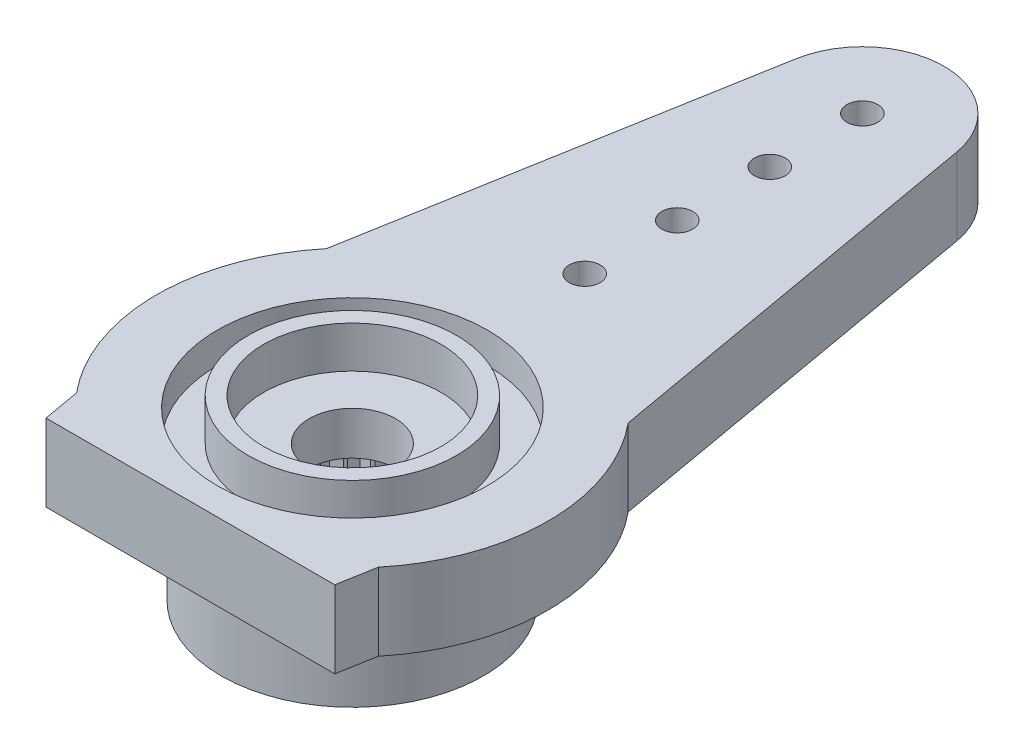
SolidWorks part; units mm, degrees
material "PC High Viscosity"
ref_plane "Front Plane" through (0, 0, 0) normal (0, 0, 1) x (1, 0, 0)
ref_plane "Top Plane" through (0, 0, 0) normal (0, 1, 0) x (1, 0, 0)
ref_plane "Right Plane" through (0, 0, 0) normal (1, 0, 0) x (0, 0, -1)
sketch "BaseS" plane through (0, 0, 0) normal (0, 1, 0) x (1, 0, 0)
  circle A0 centre (0, 0) radius 6.35
  dimension "D1" = 12.7
extrude "BASE" add sketch "BaseS" along normal blind 5.4
sketch "TopBoreS" plane through (0, 5.4, 0) normal (0, 1, 0) x (1, 0, 0)
  circle A0 centre (0, 0) radius 1.4
  dimension "D1" = 2.8
extrude "TOP BORE" cut sketch "TopBoreS" against normal through all
sketch "HornHalfS" plane through (0, 5.4, 0) normal (0, 1, 0) x (1, 0, 0)
  line L0 (0, 0) -> (0, 16.53) construction
  line L1 (-2.6097, 16.9902) -> (-4.8916, 4.049)
  line L2 (0, 19.18) -> (0, 16.53) construction
  line L3 (2.6097, 16.9902) -> (4.8916, 4.049)
  arc A0 (2.6097, 16.9902) -> (-2.6097, 16.9902) centre (0, 16.53) ccw
  arc A1 (4.8916, 4.049) -> (-4.8916, 4.049) centre (0, 0) ccw
  circle A2 centre (0, 0) radius 6.35 construction
  dimension "D1" = 5.3
  dimension "D2" = 19.18
  dimension "D3" = 10
  dimension "D4" = 9.7832
extrude "HORN HALF" add sketch "HornHalfS" against normal blind 2.5
sketch "HornAttachS" plane through (0, 5.4, 0) normal (0, 1, 0) x (1, 0, 0)
  circle A0 centre (0, 16.53) radius 0.5
  dimension "D1" = 1
extrude "HORN ATTACH" cut sketch "HornAttachS" against normal through all
sketch "HA LP RS" plane through (0, 0, 0) normal (0, 1, 0) x (1, 0, 0)
  line L0 (0, 0) -> (0, 16.53) construction
pattern_linear "HA LP" count 4 spacing 3 along (0, 0, 1) of "HORN ATTACH"
mirror "HORN BODIES" about plane through (0, 0, 0) normal (0, 0, 1) of "HA LP", "HORN ATTACH", "HORN HALF"
sketch "ToothS" plane through (0, 0, 0) normal (0, -1, 0) x (1, 0, 0)
  line L0 (0, -2.9) -> (0.2629, -2.5867)
  line L1 (0, -2.9) -> (-0.2629, -2.5867)
  line L2 (0, -2.6) -> (0, -2.9) construction
  line L3 (0, 0) -> (0, -2.6) construction
  arc A0 (-0.2629, -2.5867) -> (0.2629, -2.5867) centre (0, 0) ccw
  dimension "D1" = 5.2
  dimension "D2" = 80
  dimension "D3" = 0.3
extrude "TOOTH" cut sketch "ToothS" against normal blind 3
pattern_circular "TOOTH CP" count 26 over 360 about axis through (0, 0, 0) along (0, 1, 0) of "TOOTH"
sketch "BottomBoreS" plane through (0, 0, 0) normal (0, -1, 0) x (-1, 0, 0)
  circle A0 centre (0, 0) radius 2.6
  arc A1 (0.2629, 2.5867) -> (-0.2629, 2.5867) centre (0, 0) ccw construction
extrude "BOTTOM BORE" cut sketch "BottomBoreS" against normal up to surface (3 mm away) up to face at (-0.6451, 3, 2.6172)
sketch "HoldingShaftS" plane through (0, 0, 0) normal (0, -1, 0) x (1, 0, 0)
  circle A0 centre (0, 0) radius 6.35 construction
  circle A1 centre (0, 0) radius 6.35
  circle A2 centre (0, 0) radius 4.25
  dimension "D1" = 2.1
  dimension "D2" = 8.5
extrude "HOLDING SHAFT" cut sketch "HoldingShaftS" against normal up to surface (2.9 mm away) up to face at (0, 2.9, -13.03)
sketch "TopCutS" plane through (0, 5.4, 0) normal (0, 1, 0) x (1, 0, 0)
  circle A0 centre (0, 0) radius 4.375
  arc A1 (4.8916, -4.049) -> (4.8916, 4.049) centre (0, 0) ccw construction
  dimension "D1" = 1.975
  dimension "D2" = 8.75
extrude "TOP CUT" cut sketch "TopCutS" against normal blind 1
sketch "TopPocketCylinderS" plane through (0, 4.4, 0) normal (0, 1, 0) x (1, 0, 0)
  circle A0 centre (0, 0) radius 2.875
  circle A1 centre (0, 0) radius 3.375
  circle A2 centre (0, 0) radius 4.375 construction
  dimension "D2" = 0.5
  dimension "D1" = 1
  dimension "D3" = 6.75
extrude "TOP POCKET CYLINDER" add sketch "TopPocketCylinderS" along normal offset from surface (1.35 mm away) 0.35 up to face at (0, 5.4, 4.375) offset beyond the face yes
sketch "Sketch1" plane through (0, 5.4, 0) normal (0, 1, 0) x (1, 0, 0)
  line L0 (4.6798, -5.25) -> (2.6097, -16.9902)
  line L1 (-4.6798, -5.25) -> (-2.6097, -16.9902)
  line L3 (-4.6798, -5.25) -> (4.6798, -5.25)
  line L4 (-2.6097, -16.9902) -> (-4.8916, -4.049) construction
  arc A1 (2.6097, -16.9902) -> (-2.6097, -16.9902) centre (0, -16.53) cw
  point P0 (0, -5.25)
  point P11 (-4.6799, -5.2495)
  dimension "D1" = 5.25
extrude "Cut-Extrude1" cut sketch "Sketch1" against normal up to surface (2.5 mm away) up to face at (0, 2.9, -13.03)
